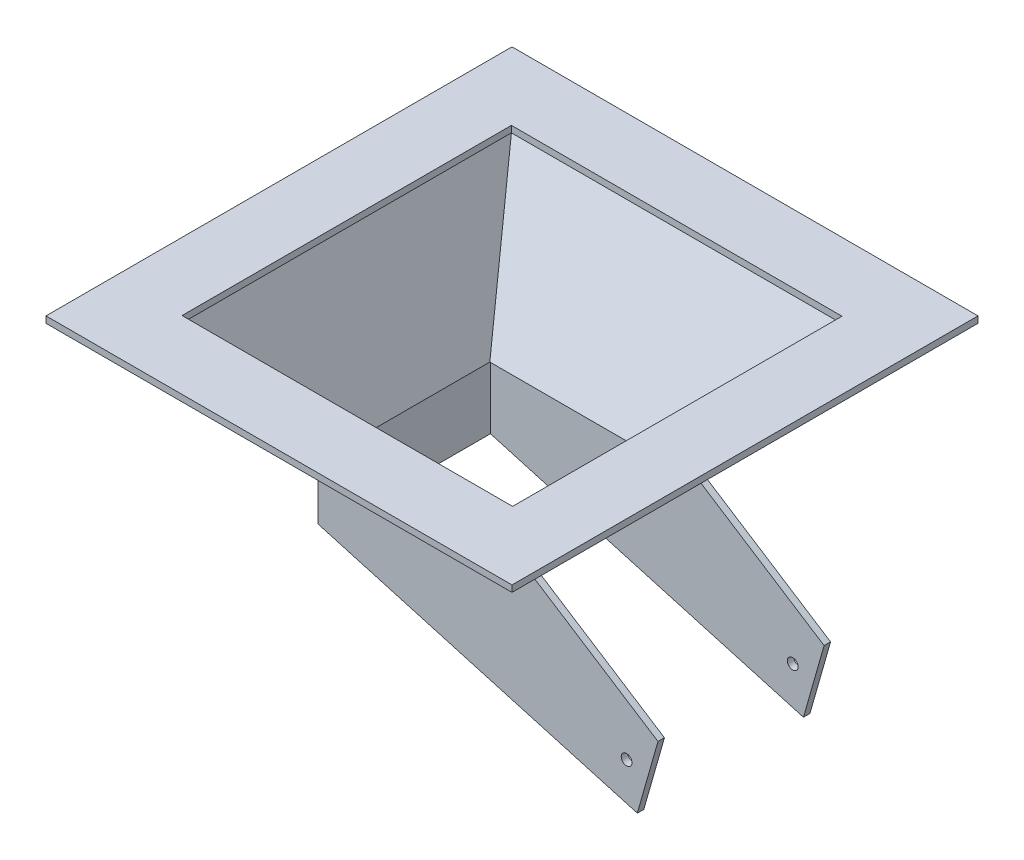
SolidWorks part; units mm, degrees
ref_plane "前视基准面" through (0, 0, 0) normal (0, 0, 1) x (1, 0, 0)
ref_plane "上视基准面" through (0, 0, 0) normal (0, 1, 0) x (1, 0, 0)
ref_plane "右视基准面" through (0, 0, 0) normal (1, 0, 0) x (0, 0, -1)
sketch "草图1" plane through (0, 0, 0) normal (0, 1, 0) x (1, 0, 0)
  line L1 (-50, -40) -> (50, -40)
  line L2 (-50, -40) -> (-50, 40)
  line L3 (-50, 40) -> (50, 40)
  line L4 (50, -40) -> (50, 40)
  line L5 (-50, -40) -> (50, 40) construction
  line L6 (-50, 40) -> (50, -40) construction
  point P0 (0, 0)
  dimension "D1" = 80
  dimension "D2" = 100
sketch "草图3" plane through (0, 0, 0) normal (0, 0, 1) x (1, 0, 0)
  line L0 (-50, 0) -> (50, 0)
  line L1 (50, 0) -> (107.6655, -37.0112)
  line L2 (107.6655, -37.0112) -> (98.0946, -70.5771)
  line L3 (98.0946, -70.5771) -> (-50, -28.4751)
  line L4 (-50, -28.4751) -> (-50, 0)
sketch "草图4" plane through (0, 0, 0) normal (0, 0, 1) x (1, 0, 0)
  line L0 (-50, 0) -> (50, 0)
  line L1 (50, 0) -> (107.6655, -37.0112)
  line L2 (107.6655, -37.0112) -> (98.0946, -70.5771)
  line L3 (98.0946, -70.5771) -> (-50, -28.4751)
  line L4 (-50, -28.4751) -> (-50, 0)
sketch "草图5" plane through (0, 0, 0) normal (0, 0, 1) x (1, 0, 0)
  line L0 (-50, 0) -> (-47, 0)
  line L1 (-47, 0) -> (-47, -29.328)
  line L2 (-47, -29.328) -> (-50, -28.4751)
  line L3 (-50, -28.4751) -> (-50, 0)
sketch "草图6" plane through (0, 0, 0) normal (0, 0, 1) x (1, 0, 0)
  circle A0 centre (93.1245, -51.5905) radius 2.5
ref_plane "Inlet Height" through (0, 57, 0) normal (0, 1, 0) x (1, 0, 0)
sketch "Inlet Profile" plane through (0, 57, 0) normal (0, 1, 0) x (1, 0, 0)
  line L1 (-80, -80) -> (80, -80)
  line L2 (-80, -80) -> (-80, 80)
  line L3 (-80, 80) -> (80, 80)
  line L4 (80, -80) -> (80, 80)
  point P4 (0, 0)
  dimension "D1" = 160
  dimension "D2" = 80
  dimension "D3" = 80
loft "Hopper Shape" add profiles "草图1", "Inlet Profile"
shell "Wall Thickness" thickness 3
sketch "Flange Profile" plane through (0, 57, 0) normal (0, 1, 0) x (1, 0, 0)
  line L0 (-76.6099, -76.335) -> (76.6099, -76.335) construction
  line L1 (-108, -108) -> (108, -108)
  line L2 (-108, -108) -> (-108, 108)
  line L3 (-108, 108) -> (108, 108)
  line L4 (108, -108) -> (108, 108)
  line L5 (76.6099, -76.335) -> (76.6099, 76.335) construction
  line L6 (76.6099, 76.335) -> (-76.6099, 76.335) construction
  line L7 (-76.6099, 76.335) -> (-76.6099, -76.335) construction
  line L8 (-76.6099, -76.335) -> (76.6099, -76.335)
  line L9 (76.6099, -76.335) -> (76.6099, 76.335)
  line L10 (76.6099, 76.335) -> (-76.6099, 76.335)
  line L11 (-76.6099, 76.335) -> (-76.6099, -76.335)
  point P6 (0, 0)
  dimension "D1" = 216
  dimension "D2" = 108
  dimension "D3" = 108
extrude "Mounting Flange" add sketch "Flange Profile" along normal blind 3
extrude "Outlet Side Front" add sketch "草图3" along normal blind 3 from offset 37
extrude "Outlet Side Rear" add sketch "草图4" against normal blind 3 from offset 37
extrude "Outlet Back" add sketch "草图5" along normal mid plane 80
extrude "Joint Fixing Holes" cut sketch "草图6" against normal mid plane 80
